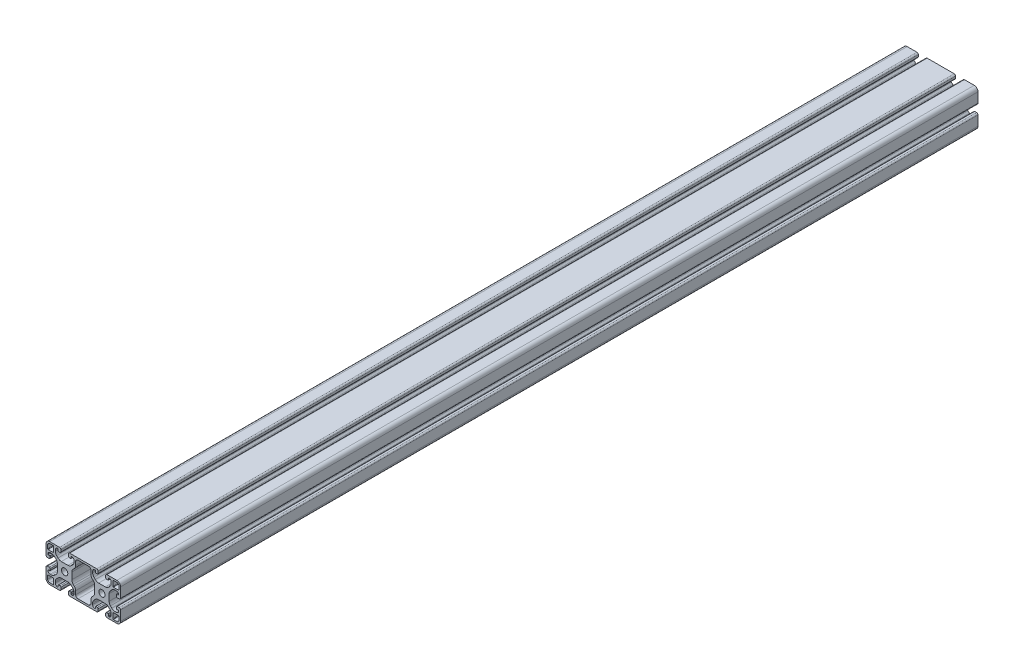
SolidWorks part; units mm, degrees
ref_plane "Plan de face" through (0, 0, 0) normal (0, 0, 1) x (1, 0, 0)
ref_plane "Plan de dessus" through (0, 0, 0) normal (0, 1, 0) x (1, 0, 0)
ref_plane "Plan de droite" through (0, 0, 0) normal (1, 0, 0) x (0, 0, -1)
ref_plane "Plan1" through (0, 0, 20) normal (0, 0, 1) x (1, 0, 0)
sketch "Esquisse1" plane through (0, 0, 20) normal (0, 0, 1) x (1, 0, 0)
  line L0 (66.5, 4.5) -> (65, 4.5)
  line L1 (64, 3.5) -> (64, 1.5)
  line L2 (65.5, 0) -> (76, 0)
  line L3 (80, 4) -> (80, 14.5)
  line L4 (78.5, 16) -> (76.5, 16)
  line L5 (75.5, 15) -> (75.5, 13.5)
  line L6 (76, 13) -> (77.5, 13)
  line L7 (75.5, 10) -> (74.1924, 10)
  line L8 (70.6569, 11.4645) -> (69.2145, 12.9069)
  line L9 (67.75, 16.4424) -> (67.75, 23.5576)
  line L10 (69.2145, 27.0931) -> (70.6569, 28.5355)
  line L11 (74.1924, 30) -> (75.5, 30)
  line L12 (77.5, 27) -> (76, 27)
  line L13 (75.5, 26.5) -> (75.5, 25)
  line L14 (76.5, 24) -> (78.5, 24)
  line L15 (80, 25.5) -> (80, 36)
  line L16 (76, 40) -> (65.5, 40)
  line L17 (64, 38.5) -> (64, 36.5)
  line L18 (65, 35.5) -> (66.5, 35.5)
  line L19 (67, 36) -> (67, 37.5)
  line L20 (70, 35.5) -> (70, 34.1924)
  line L21 (68.5355, 30.6569) -> (67.0931, 29.2145)
  line L22 (63.5576, 27.75) -> (56.4424, 27.75)
  line L23 (52.9069, 29.2145) -> (51.4645, 30.6569)
  line L24 (50, 34.1924) -> (50, 35.5)
  line L25 (53, 37.5) -> (53, 36)
  line L26 (53.5, 35.5) -> (55, 35.5)
  line L27 (56, 36.5) -> (56, 38.5)
  line L28 (54.5, 40) -> (25.5, 40)
  line L29 (24, 38.5) -> (24, 36.5)
  line L30 (25, 35.5) -> (26.5, 35.5)
  line L31 (27, 36) -> (27, 37.5)
  line L32 (30, 35.5) -> (30, 34.1924)
  line L33 (28.5355, 30.6569) -> (27.0931, 29.2145)
  line L34 (23.5576, 27.75) -> (16.4424, 27.75)
  line L35 (12.9069, 29.2145) -> (11.4645, 30.6569)
  line L36 (10, 34.1924) -> (10, 35.5)
  line L37 (13, 37.5) -> (13, 36)
  line L38 (13.5, 35.5) -> (15, 35.5)
  line L39 (16, 36.5) -> (16, 38.5)
  line L40 (14.5, 40) -> (4, 40)
  line L41 (0, 36) -> (0, 25.5)
  line L42 (1.5, 24) -> (3.5, 24)
  line L43 (4.5, 25) -> (4.5, 26.5)
  line L44 (4, 27) -> (2.5, 27)
  line L45 (4.5, 30) -> (5.8076, 30)
  line L46 (9.3431, 28.5355) -> (10.7855, 27.0931)
  line L47 (12.25, 23.5576) -> (12.25, 16.4424)
  line L48 (10.7855, 12.9069) -> (9.3431, 11.4645)
  line L49 (5.8076, 10) -> (4.5, 10)
  line L50 (2.5, 13) -> (4, 13)
  line L51 (4.5, 13.5) -> (4.5, 15)
  line L52 (3.5, 16) -> (1.5, 16)
  line L53 (0, 14.5) -> (0, 4)
  line L54 (4, 0) -> (14.5, 0)
  line L55 (16, 1.5) -> (16, 3.5)
  line L56 (15, 4.5) -> (13.5, 4.5)
  line L57 (13, 4) -> (13, 2.5)
  line L58 (10, 4.5) -> (10, 5.8076)
  line L59 (11.4645, 9.3431) -> (12.9069, 10.7855)
  line L60 (16.4424, 12.25) -> (23.5576, 12.25)
  line L61 (27.0931, 10.7855) -> (28.5355, 9.3431)
  line L62 (30, 5.8076) -> (30, 4.5)
  line L63 (27, 2.5) -> (27, 4)
  line L64 (26.5, 4.5) -> (25, 4.5)
  line L65 (24, 3.5) -> (24, 1.5)
  line L66 (25.5, 0) -> (54.5, 0)
  line L67 (56, 1.5) -> (56, 3.5)
  line L68 (55, 4.5) -> (53.5, 4.5)
  line L69 (53, 4) -> (53, 2.5)
  line L70 (50, 4.5) -> (50, 5.8076)
  line L71 (51.4645, 9.3431) -> (52.9069, 10.7855)
  line L72 (56.4424, 12.25) -> (63.5576, 12.25)
  line L73 (67.0931, 10.7855) -> (68.5355, 9.3431)
  line L74 (70, 5.8076) -> (70, 4.5)
  line L75 (67, 2.5) -> (67, 4)
  line L76 (31.8, 4.5) -> (31.8, 8.2503)
  line L77 (30.3355, 11.7858) -> (29.2145, 12.9069)
  line L78 (27.75, 16.4424) -> (27.75, 23.5576)
  line L79 (29.2145, 27.0931) -> (30.3355, 28.2142)
  line L80 (31.8, 31.7497) -> (31.8, 35.5)
  line L81 (34.3, 38) -> (45.7, 38)
  line L82 (48.2, 35.5) -> (48.2, 31.7497)
  line L83 (49.6645, 28.2142) -> (50.7855, 27.0931)
  line L84 (52.25, 23.5576) -> (52.25, 16.4424)
  line L85 (50.7855, 12.9069) -> (49.6645, 11.7858)
  line L86 (48.2, 8.2503) -> (48.2, 4.5)
  line L87 (45.7, 2) -> (34.3, 2)
  line L88 (7.7, 1.8) -> (4, 1.8)
  line L89 (1.8, 4) -> (1.8, 7.7)
  line L90 (2.3, 8.2) -> (7.7, 8.2)
  line L91 (8.2, 7.7) -> (8.2, 2.3)
  line L92 (72.3, 38.2) -> (76, 38.2)
  line L93 (78.2, 36) -> (78.2, 32.3)
  line L94 (77.7, 31.8) -> (72.3, 31.8)
  line L95 (71.8, 32.3) -> (71.8, 37.7)
  line L96 (78.2, 7.7) -> (78.2, 4)
  line L97 (76, 1.8) -> (72.3, 1.8)
  line L98 (71.8, 2.3) -> (71.8, 7.7)
  line L99 (72.3, 8.2) -> (77.7, 8.2)
  line L100 (1.8, 32.3) -> (1.8, 36)
  line L101 (4, 38.2) -> (7.7, 38.2)
  line L102 (8.2, 37.7) -> (8.2, 32.3)
  line L103 (7.7, 31.8) -> (2.3, 31.8)
  arc A0 (67, 4) -> (66.5, 4.5) centre (66.5, 4) ccw
  arc A1 (65, 4.5) -> (64, 3.5) centre (65, 3.5) ccw
  arc A2 (64, 1.5) -> (65.5, 0) centre (65.5, 1.5) ccw
  arc A3 (76, 0) -> (80, 4) centre (76, 4) ccw
  arc A4 (80, 14.5) -> (78.5, 16) centre (78.5, 14.5) ccw
  arc A5 (76.5, 16) -> (75.5, 15) centre (76.5, 15) ccw
  arc A6 (75.5, 13.5) -> (76, 13) centre (76, 13.5) ccw
  arc A7 (77.5, 13) -> (78, 12.5) centre (77.5, 12.5) cw
  arc A8 (78, 12.5) -> (75.5, 10) centre (75.5, 12.5) cw
  arc A9 (74.1924, 10) -> (70.6569, 11.4645) centre (74.1924, 15) cw
  arc A10 (69.2145, 12.9069) -> (67.75, 16.4424) centre (72.75, 16.4424) cw
  arc A11 (67.75, 23.5576) -> (69.2145, 27.0931) centre (72.75, 23.5576) cw
  arc A12 (70.6569, 28.5355) -> (74.1924, 30) centre (74.1924, 25) cw
  arc A13 (75.5, 30) -> (78, 27.5) centre (75.5, 27.5) cw
  arc A14 (78, 27.5) -> (77.5, 27) centre (77.5, 27.5) cw
  arc A15 (76, 27) -> (75.5, 26.5) centre (76, 26.5) ccw
  arc A16 (75.5, 25) -> (76.5, 24) centre (76.5, 25) ccw
  arc A17 (78.5, 24) -> (80, 25.5) centre (78.5, 25.5) ccw
  arc A18 (80, 36) -> (76, 40) centre (76, 36) ccw
  arc A19 (65.5, 40) -> (64, 38.5) centre (65.5, 38.5) ccw
  arc A20 (64, 36.5) -> (65, 35.5) centre (65, 36.5) ccw
  arc A21 (66.5, 35.5) -> (67, 36) centre (66.5, 36) ccw
  arc A22 (67, 37.5) -> (67.5, 38) centre (67.5, 37.5) cw
  arc A23 (67.5, 38) -> (70, 35.5) centre (67.5, 35.5) cw
  arc A24 (70, 34.1924) -> (68.5355, 30.6569) centre (65, 34.1924) cw
  arc A25 (67.0931, 29.2145) -> (63.5576, 27.75) centre (63.5576, 32.75) cw
  arc A26 (56.4424, 27.75) -> (52.9069, 29.2145) centre (56.4424, 32.75) cw
  arc A27 (51.4645, 30.6569) -> (50, 34.1924) centre (55, 34.1924) cw
  arc A28 (50, 35.5) -> (52.5, 38) centre (52.5, 35.5) cw
  arc A29 (52.5, 38) -> (53, 37.5) centre (52.5, 37.5) cw
  arc A30 (53, 36) -> (53.5, 35.5) centre (53.5, 36) ccw
  arc A31 (55, 35.5) -> (56, 36.5) centre (55, 36.5) ccw
  arc A32 (56, 38.5) -> (54.5, 40) centre (54.5, 38.5) ccw
  arc A33 (25.5, 40) -> (24, 38.5) centre (25.5, 38.5) ccw
  arc A34 (24, 36.5) -> (25, 35.5) centre (25, 36.5) ccw
  arc A35 (26.5, 35.5) -> (27, 36) centre (26.5, 36) ccw
  arc A36 (27, 37.5) -> (27.5, 38) centre (27.5, 37.5) cw
  arc A37 (27.5, 38) -> (30, 35.5) centre (27.5, 35.5) cw
  arc A38 (30, 34.1924) -> (28.5355, 30.6569) centre (25, 34.1924) cw
  arc A39 (27.0931, 29.2145) -> (23.5576, 27.75) centre (23.5576, 32.75) cw
  arc A40 (16.4424, 27.75) -> (12.9069, 29.2145) centre (16.4424, 32.75) cw
  arc A41 (11.4645, 30.6569) -> (10, 34.1924) centre (15, 34.1924) cw
  arc A42 (10, 35.5) -> (12.5, 38) centre (12.5, 35.5) cw
  arc A43 (12.5, 38) -> (13, 37.5) centre (12.5, 37.5) cw
  arc A44 (13, 36) -> (13.5, 35.5) centre (13.5, 36) ccw
  arc A45 (15, 35.5) -> (16, 36.5) centre (15, 36.5) ccw
  arc A46 (16, 38.5) -> (14.5, 40) centre (14.5, 38.5) ccw
  arc A47 (4, 40) -> (0, 36) centre (4, 36) ccw
  arc A48 (0, 25.5) -> (1.5, 24) centre (1.5, 25.5) ccw
  arc A49 (3.5, 24) -> (4.5, 25) centre (3.5, 25) ccw
  arc A50 (4.5, 26.5) -> (4, 27) centre (4, 26.5) ccw
  arc A51 (2.5, 27) -> (2, 27.5) centre (2.5, 27.5) cw
  arc A52 (2, 27.5) -> (4.5, 30) centre (4.5, 27.5) cw
  arc A53 (5.8076, 30) -> (9.3431, 28.5355) centre (5.8076, 25) cw
  arc A54 (10.7855, 27.0931) -> (12.25, 23.5576) centre (7.25, 23.5576) cw
  arc A55 (12.25, 16.4424) -> (10.7855, 12.9069) centre (7.25, 16.4424) cw
  arc A56 (9.3431, 11.4645) -> (5.8076, 10) centre (5.8076, 15) cw
  arc A57 (4.5, 10) -> (2, 12.5) centre (4.5, 12.5) cw
  arc A58 (2, 12.5) -> (2.5, 13) centre (2.5, 12.5) cw
  arc A59 (4, 13) -> (4.5, 13.5) centre (4, 13.5) ccw
  arc A60 (4.5, 15) -> (3.5, 16) centre (3.5, 15) ccw
  arc A61 (1.5, 16) -> (0, 14.5) centre (1.5, 14.5) ccw
  arc A62 (0, 4) -> (4, 0) centre (4, 4) ccw
  arc A63 (14.5, 0) -> (16, 1.5) centre (14.5, 1.5) ccw
  arc A64 (16, 3.5) -> (15, 4.5) centre (15, 3.5) ccw
  arc A65 (13.5, 4.5) -> (13, 4) centre (13.5, 4) ccw
  arc A66 (13, 2.5) -> (12.5, 2) centre (12.5, 2.5) cw
  arc A67 (12.5, 2) -> (10, 4.5) centre (12.5, 4.5) cw
  arc A68 (10, 5.8076) -> (11.4645, 9.3431) centre (15, 5.8076) cw
  arc A69 (12.9069, 10.7855) -> (16.4424, 12.25) centre (16.4424, 7.25) cw
  arc A70 (23.5576, 12.25) -> (27.0931, 10.7855) centre (23.5576, 7.25) cw
  arc A71 (28.5355, 9.3431) -> (30, 5.8076) centre (25, 5.8076) cw
  arc A72 (30, 4.5) -> (27.5, 2) centre (27.5, 4.5) cw
  arc A73 (27.5, 2) -> (27, 2.5) centre (27.5, 2.5) cw
  arc A74 (27, 4) -> (26.5, 4.5) centre (26.5, 4) ccw
  arc A75 (25, 4.5) -> (24, 3.5) centre (25, 3.5) ccw
  arc A76 (24, 1.5) -> (25.5, 0) centre (25.5, 1.5) ccw
  arc A77 (54.5, 0) -> (56, 1.5) centre (54.5, 1.5) ccw
  arc A78 (56, 3.5) -> (55, 4.5) centre (55, 3.5) ccw
  arc A79 (53.5, 4.5) -> (53, 4) centre (53.5, 4) ccw
  arc A80 (53, 2.5) -> (52.5, 2) centre (52.5, 2.5) cw
  arc A81 (52.5, 2) -> (50, 4.5) centre (52.5, 4.5) cw
  arc A82 (50, 5.8076) -> (51.4645, 9.3431) centre (55, 5.8076) cw
  arc A83 (52.9069, 10.7855) -> (56.4424, 12.25) centre (56.4424, 7.25) cw
  arc A84 (63.5576, 12.25) -> (67.0931, 10.7855) centre (63.5576, 7.25) cw
  arc A85 (68.5355, 9.3431) -> (70, 5.8076) centre (65, 5.8076) cw
  arc A86 (70, 4.5) -> (67.5, 2) centre (67.5, 4.5) cw
  arc A87 (67.5, 2) -> (67, 2.5) centre (67.5, 2.5) cw
  circle A88 centre (20, 20) radius 3.4
  circle A89 centre (60, 20) radius 3.4
  arc A90 (34.3, 2) -> (31.8, 4.5) centre (34.3, 4.5) cw
  arc A91 (31.8, 8.2503) -> (30.3355, 11.7858) centre (26.8, 8.2503) ccw
  arc A92 (29.2145, 12.9069) -> (27.75, 16.4424) centre (32.75, 16.4424) cw
  arc A93 (27.75, 23.5576) -> (29.2145, 27.0931) centre (32.75, 23.5576) cw
  arc A94 (30.3355, 28.2142) -> (31.8, 31.7497) centre (26.8, 31.7497) ccw
  arc A95 (31.8, 35.5) -> (34.3, 38) centre (34.3, 35.5) cw
  arc A96 (45.7, 38) -> (48.2, 35.5) centre (45.7, 35.5) cw
  arc A97 (48.2, 31.7497) -> (49.6645, 28.2142) centre (53.2, 31.7497) ccw
  arc A98 (50.7855, 27.0931) -> (52.25, 23.5576) centre (47.25, 23.5576) cw
  arc A99 (52.25, 16.4424) -> (50.7855, 12.9069) centre (47.25, 16.4424) cw
  arc A100 (49.6645, 11.7858) -> (48.2, 8.2503) centre (53.2, 8.2503) ccw
  arc A101 (48.2, 4.5) -> (45.7, 2) centre (45.7, 4.5) cw
  arc A102 (8.2, 2.3) -> (7.7, 1.8) centre (7.7, 2.3) cw
  arc A103 (4, 1.8) -> (1.8, 4) centre (4, 4) cw
  arc A104 (1.8, 7.7) -> (2.3, 8.2) centre (2.3, 7.7) cw
  arc A105 (7.7, 8.2) -> (8.2, 7.7) centre (7.7, 7.7) cw
  arc A106 (71.8, 37.7) -> (72.3, 38.2) centre (72.3, 37.7) cw
  arc A107 (76, 38.2) -> (78.2, 36) centre (76, 36) cw
  arc A108 (78.2, 32.3) -> (77.7, 31.8) centre (77.7, 32.3) cw
  arc A109 (72.3, 31.8) -> (71.8, 32.3) centre (72.3, 32.3) cw
  arc A110 (77.7, 8.2) -> (78.2, 7.7) centre (77.7, 7.7) cw
  arc A111 (78.2, 4) -> (76, 1.8) centre (76, 4) cw
  arc A112 (72.3, 1.8) -> (71.8, 2.3) centre (72.3, 2.3) cw
  arc A113 (71.8, 7.7) -> (72.3, 8.2) centre (72.3, 7.7) cw
  arc A114 (2.3, 31.8) -> (1.8, 32.3) centre (2.3, 32.3) cw
  arc A115 (1.8, 36) -> (4, 38.2) centre (4, 36) cw
  arc A116 (7.7, 38.2) -> (8.2, 37.7) centre (7.7, 37.7) cw
  arc A117 (8.2, 32.3) -> (7.7, 31.8) centre (7.7, 32.3) cw
extrude "Boss.-Extru.1" add sketch "Esquisse1" against normal blind 920
